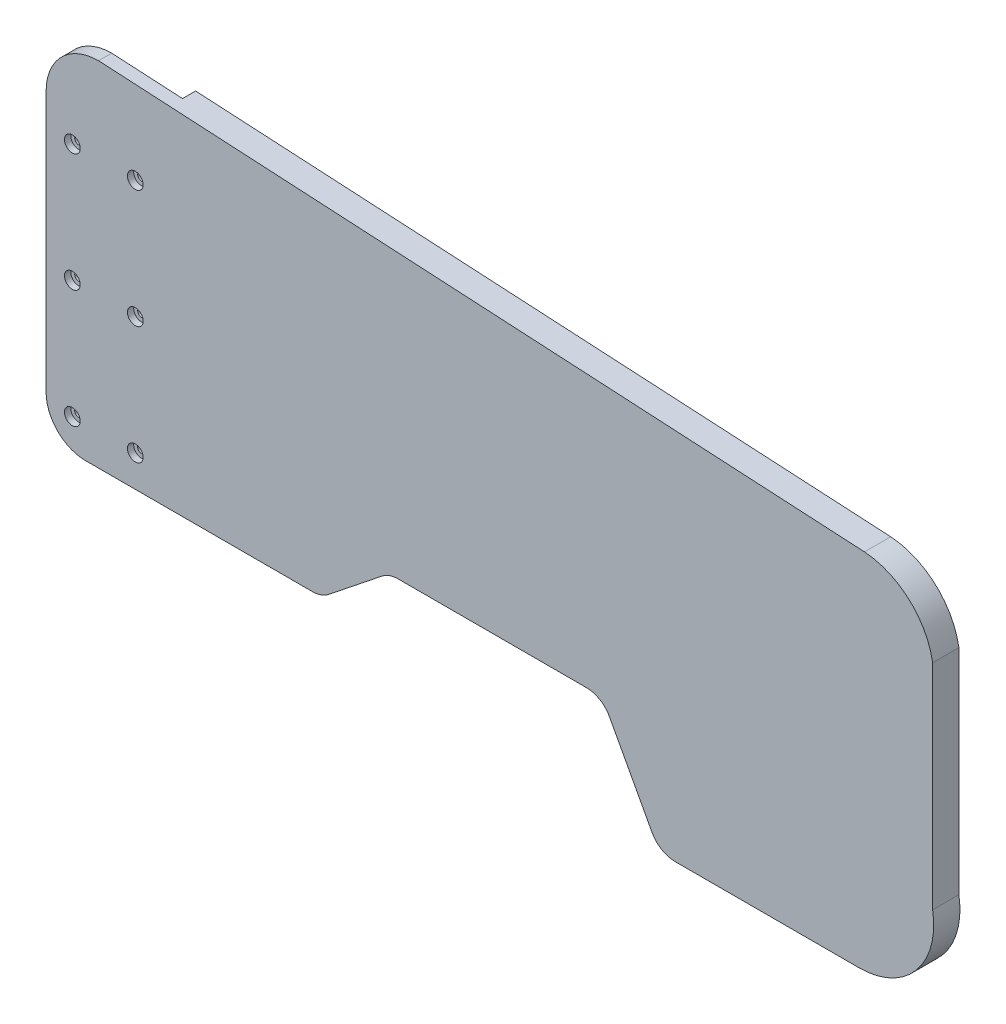
SolidWorks part; units mm, degrees
other "Folder spoin"
material "Stop 1060"
ref_plane "Płaszczyzna przednia" through (0, 0, 0) normal (0, 0, 1) x (1, 0, 0)
ref_plane "Płaszczyzna górna" through (0, 0, 0) normal (0, 1, 0) x (1, 0, 0)
ref_plane "Płaszczyzna prawa" through (0, 0, 0) normal (1, 0, 0) x (0, 0, -1)
sketch "outer-wire" plane through (0, 0, 0) normal (0, 0, 1) x (1, 0, 0)
  line L0 (-24, -24.5302) -> (62.5, -24.5302)
  line L3 (-39, -9.5302) -> (-39, 90)
  line L4 (95.2361, -4) -> (167, -4)
  line L6 (176, -9.6411) -> (192, -39.2805)
  line L7 (68.7361, -22.3476) -> (89, -6.1826)
  line L10 (271, -44.5302) -> (200.7997, -44.5302)
  line L12 (299, -11.3778) -> (299, 70.2365)
  line L14 (-19, 110) -> (273, 93.8273)
  arc A0 (-39, -9.5302) -> (-24, -24.5302) centre (-24, -9.5302) ccw
  arc A1 (-19, 110) -> (-39, 90) centre (-19, 90) ccw
  arc A2 (62.5, -24.5302) -> (68.7361, -22.3476) centre (62.5, -14.5302) ccw
  arc A3 (89, -6.1826) -> (95.2361, -4) centre (95.2361, -14) cw
  arc A4 (271, -44.5302) -> (299, -11.3778) centre (271, -16.1298) ccw
  arc A5 (299, 70.2365) -> (273, 93.8273) centre (271, 65.5) ccw
  arc A6 (200.7997, -44.5302) -> (192, -39.2805) centre (200.7997, -34.5302) cw
  arc A7 (176, -9.6411) -> (167, -4) centre (167, -14) ccw
  point P14 (66, -24.5302)
  dimension "D2" = 20
  dimension "D1" = 15
  dimension "D7" = 66
  dimension "D8" = 89
  dimension "D10" = 167
  dimension "D17" = 271
  dimension "D18" = 273
  dimension "D20" = 39
  dimension "D21" = 110
  dimension "D4" = 28.4004
  dimension "D6" = 62.5
  dimension "D9" = 167
  dimension "D12" = 192
  dimension "D11" = 176
  dimension "D3" = 10
  dimension "D5" = 28.3978
  dimension "D13" = 65.5
  dimension "D14" = 4
  dimension "D15" = 71.7639
  dimension "D16" = 271
  dimension "D19" = 299
extrude "Dodanie-wyciągnięcie1" add sketch "outer-wire" along normal blind 5 contours L0 A2 L7 A3 L4 A7 L6 A6 L10 A4 L12 A5 L14 A1 L3 A0
ref_plane "Płaszczyzna6" through (0, -24.5302, 0) normal (0, -1, 0) x (-1, 0, 0)
sketch "Szkic1" plane through (0, -24.5302, 0) normal (0, -1, 0) x (-1, 0, 0)
  line L1 (24, -5) -> (24, 0) construction
  line L2 (24, -5) -> (-62.5, -5) construction
  circle A0 centre (19, 0) radius 3.5
  dimension "D1" = 7
  dimension "D2" = 5
  dimension "D3" = 5
extrude "Wytnij-wyciągnięcie1" cut sketch "Szkic1" against normal blind 88.4
ref_plane "Płaszczyzna12" through (0, 0, 5) normal (0, 0, 1) x (1, 0, 0)
sketch "Szkic3" plane through (0, 0, 5) normal (0, 0, 1) x (1, 0, 0)
  circle A2 centre (-5, 77.5) radius 1.5
  circle A3 centre (-29, 77.5) radius 1.5
  circle A4 centre (-29, -12.5) radius 1.5
  circle A5 centre (-29, 32.5) radius 1.5
  circle A6 centre (-5, 32.5) radius 1.5
  circle A7 centre (-5, -12.5) radius 1.5
  dimension "D6" = 45
  dimension "D2" = 12.5
  dimension "D3" = 24
  dimension "D4" = 45
  dimension "D5" = 45
  dimension "D7" = 5
extrude "Wytnij-wyciągnięcie3" cut sketch "Szkic3" along direction (0, 0, 1) on the side against the normal blind 5
ref_plane "Płaszczyzna13" through (0, 0, 5) normal (0, 0, 1) x (1, 0, 0)
sketch "Szkic5" plane through (0, 0, 5) normal (0, 0, 1) x (1, 0, 0)
  circle A0 centre (-29, -12.5) radius 3
  circle A1 centre (-29, 32.5) radius 3
  circle A2 centre (-29, 77.5) radius 3
  circle A3 centre (-5, 77.5) radius 3
  circle A4 centre (-5, 32.5) radius 3
  circle A5 centre (-5, -12.5) radius 3
  dimension "D2" = 24
  dimension "D3" = 45
  dimension "D4" = 45
extrude "Wytnij-wyciągnięcie4" cut sketch "Szkic5" against normal blind 2.4 contours A0
sketch "Szkic6" plane through (0, 0, 0) normal (0, 0, -1) x (-1, 0, 0)
  line L0 (-8, -24.5302) -> (-8, 108.5046)
  line L1 (15.5, -24.5302) -> (-62.5, -24.5302) construction
  line L2 (19, 110) -> (-273, 93.8273) construction
  line L3 (-8, -24.5302) -> (-62.5, -24.5302)
  line L4 (-68.7361, -22.3476) -> (-89, -6.1826)
  line L5 (-95.2361, -4) -> (-167, -4)
  line L6 (-176, -9.6411) -> (-192, -39.2805)
  line L7 (-200.7997, -44.5302) -> (-271, -44.5302)
  line L8 (-299, -11.3778) -> (-299, 70.2365)
  line L9 (-273, 93.8273) -> (-8, 108.5046)
  line L10 (39, -9.5302) -> (39, 90) construction
  line L11 (24, -24.5302) -> (22.5, -24.5302) construction
  arc A0 (-68.7361, -22.3476) -> (-62.5, -24.5302) centre (-62.5, -14.5302) ccw
  arc A1 (-95.2361, -4) -> (-89, -6.1826) centre (-95.2361, -14) cw
  arc A2 (-299, -11.3778) -> (-271, -44.5302) centre (-271, -16.1298) ccw
  arc A3 (-273, 93.8273) -> (-299, 70.2365) centre (-271, 65.5) ccw
  arc A4 (-192, -39.2805) -> (-200.7997, -44.5302) centre (-200.7997, -34.5302) cw
  arc A5 (-167, -4) -> (-176, -9.6411) centre (-167, -14) ccw
  dimension "D1" = 15
  dimension "D2" = 47
extrude "Dodanie-wyciągnięcie2" add sketch "Szkic6" along normal blind 5
ref_plane "Płaszczyzna14" through (0, 65.3698, 0) normal (0, -1, 0) x (-1, 0, 0)
sketch "Szkic7" plane through (0, 65.3698, 0) normal (0, -1, 0) x (-1, 0, 0)
  circle A0 centre (19, 0) radius 3.5
  dimension "D1" = 7
extrude "Wytnij-wyciągnięcie5" cut sketch "Szkic7" against normal blind 5
ref_plane "Płaszczyzna15" through (0, 73.3698, 0) normal (0, -1, 0) x (-1, 0, 0)
sketch "Szkic8" plane through (0, 73.3698, 0) normal (0, -1, 0) x (-1, 0, 0)
  circle A0 centre (19, 0) radius 3.5
  dimension "D1" = 7
extrude "Wytnij-wyciągnięcie6" cut sketch "Szkic8" against normal blind 5
sketch "Szkic9" plane through (0, 73.3698, 0) normal (0, -1, 0) x (-1, 0, 0)
  line L0 (22.5, 0) -> (15.5, 0) construction
  circle A0 centre (19, 0) radius 1.5
  dimension "D1" = 3
extrude "Wytnij-wyciągnięcie7" cut sketch "Szkic9" along normal blind 3 contours A0
sketch "Szkic10" plane through (0, 65.3698, 0) normal (0, -1, 0) x (-1, 0, 0)
  line L0 (22.5, 0) -> (15.5, 0) construction
  circle A0 centre (19, 0) radius 2.85
  dimension "D1" = 5.7
extrude "Wytnij-wyciągnięcie8" cut sketch "Szkic10" along normal blind 2 contours A0
sketch "Szkic11" plane through (0, 0, 0) normal (0, 0, -1) x (-1, 0, 0)
  line L1 (22.5, 73.3698) -> (15.5, 73.3698)
  line L2 (22.5, 73.3698) -> (22.5, 78.3698)
  line L3 (22.5, 78.3698) -> (15.5, 78.3698)
  line L4 (15.5, 73.3698) -> (15.5, 78.3698)
  line L5 (22.5, 70.3698) -> (15.5, 70.3698)
  line L6 (22.5, 70.3698) -> (22.5, 65.3698)
  line L7 (22.5, 65.3698) -> (15.5, 65.3698)
  line L8 (15.5, 70.3698) -> (15.5, 65.3698)
extrude "Wytnij-wyciągnięcie9" cut sketch "Szkic11" against normal blind 3.5
